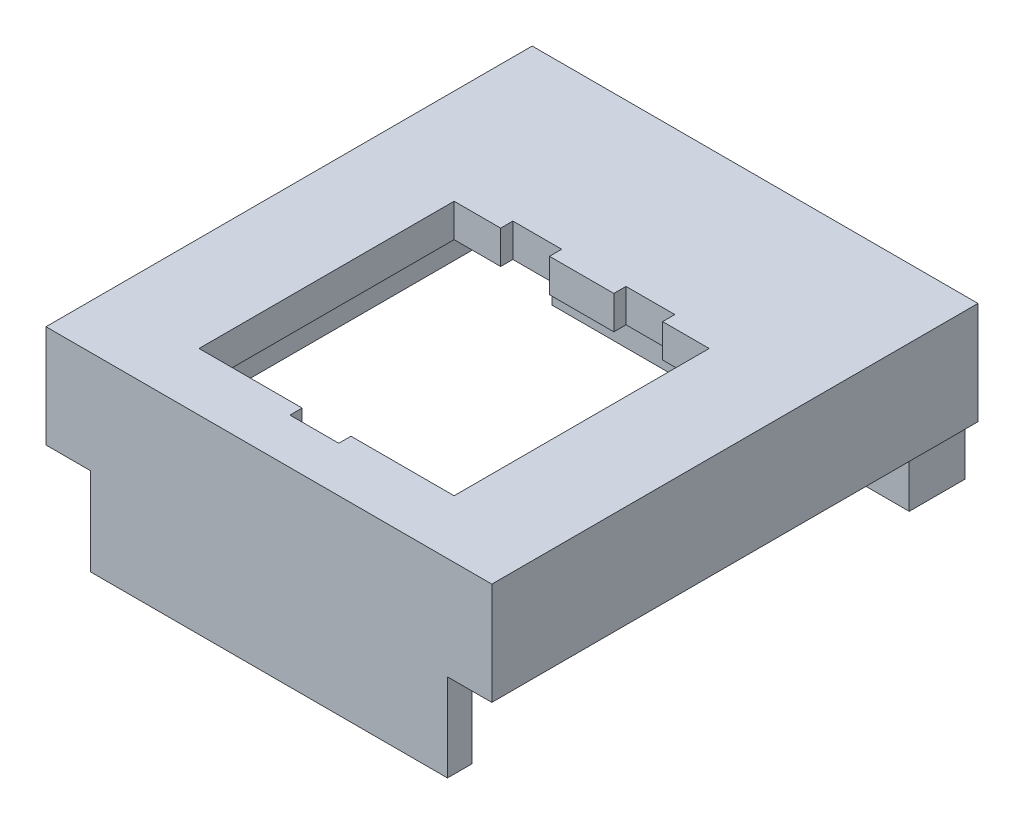
SolidWorks part; units mm, degrees
material "Custom Plastic"
ref_plane "Front Plane" through (0, 0, 0) normal (0, 0, 1) x (1, 0, 0)
ref_plane "Top Plane" through (0, 0, 0) normal (0, 1, 0) x (1, 0, 0)
ref_plane "Right Plane" through (0, 0, 0) normal (1, 0, 0) x (0, 0, -1)
sketch "Sketch1" plane through (0, 0, 0) normal (0, 1, 0) x (1, 0, 0)
  line L0 (-8.05, 10.21) -> (-8.05, -10.21)
  line L1 (8.05, -10.21) -> (8.05, 10.21)
  line L3 (10.05, -10.21) -> (10.05, 10.21)
  line L4 (-10.05, 10.21) -> (-10.05, -10.21)
  line L5 (-8.05, -10.21) -> (-10.05, -10.21)
  line L6 (8.05, -10.21) -> (10.05, -10.21)
  line L7 (-8.05, 10.21) -> (-10.05, 10.21)
  line L8 (8.05, 10.21) -> (10.05, 10.21)
  dimension "D1" = 8.05
  dimension "D2" = 10.05
  dimension "D3" = 8.05
  dimension "D4" = 10.21
  dimension "D5" = 10.21
extrude "Boss-Extrude1" add sketch "Sketch1" along normal blind 4.62
sketch "Sketch2" plane through (0, 4.62, 0) normal (0, 1, 0) x (1, 0, 0)
  line L0 (-8.05, -10.21) -> (8.05, -10.21)
  line L1 (-8.05, -9.11) -> (8.05, -9.11)
  line L2 (8.05, 10.21) -> (8.05, -10.21) construction
  line L3 (-8.05, -10.21) -> (-8.05, 10.21) construction
  line L4 (8.05, -9.11) -> (8.05, -10.21)
  line L5 (-8.05, -10.21) -> (-8.05, -9.11)
  dimension "D1" = 1.1
extrude "Boss-Extrude2" add sketch "Sketch2" against normal blind 8.57
sketch "Sketch3" plane through (0, 4.62, 0) normal (0, 1, 0) x (1, 0, 0)
  line L0 (-10.05, 10.21) -> (10.05, 10.21)
  line L2 (10.05, 11.71) -> (-10.05, 11.71)
  line L4 (-10.05, 10.21) -> (-10.05, 11.71)
  line L6 (10.05, 10.21) -> (10.05, 11.71)
  dimension "D1" = 1.5
extrude "Boss-Extrude3" add sketch "Sketch3" against normal blind 4.62
sketch "Sketch4" plane through (0, 0, 0) normal (0, -1, 0) x (1, 0, 0)
  line L0 (-8.05, -10.21) -> (8.05, -10.21) construction
  line L1 (-8.05, -10.21) -> (8.05, -10.21)
  line L2 (-8.05, -10.21) -> (-8.05, -11.71)
  line L3 (10.05, -11.71) -> (-10.05, -11.71) construction
  line L4 (-8.05, -11.71) -> (8.05, -11.71)
  line L5 (8.05, -11.71) -> (8.05, -10.21)
extrude "Boss-Extrude4" add sketch "Sketch4" along normal blind 3.95
sketch "Sketch5" plane through (-8.05, 0, 0) normal (1, 0, 0) x (0, 0, -1)
  line L0 (-9.11, 3.12) -> (10.21, 3.12)
  line L4 (-9.11, 4.62) -> (-9.11, 0)
  line L5 (-9.11, 0) -> (10.21, 0)
  line L6 (10.21, 0) -> (10.21, 4.62)
  line L7 (10.21, 4.62) -> (-9.11, 4.62)
  line L8 (-9.11, 4.62) -> (-9.11, 3.12)
  line L10 (10.21, 3.12) -> (10.21, 4.62)
  line L11 (10.21, 4.62) -> (-9.11, 4.62)
  dimension "D2" = 1.5
  dimension "D1" = 0
extrude "Boss-Extrude5" add sketch "Sketch5" along normal up to surface (16.1 mm away) up to face at (8.05, 2.31, -0.55)
sketch "Sketch6" plane through (0, 4.62, 0) normal (0, 1, 0) x (1, 0, 0)
  line L0 (5.75, -7.61) -> (-5.75, -7.61)
  line L1 (5.75, -7.61) -> (5.75, 3.89)
  line L2 (-5.75, 3.89) -> (5.75, 3.89)
  line L3 (-5.75, -7.61) -> (-5.75, 3.89)
  line L5 (-10.05, -10.21) -> (10.05, -10.21) construction
  line L6 (8.05, 10.21) -> (8.05, -9.11) construction
  dimension "D1" = 11.5
  dimension "D2" = 11.5
  dimension "D3" = 2.6
  dimension "D4" = 2.3
extrude "Cut-Extrude1" cut sketch "Sketch6" against normal through all
sketch "Sketch8" plane through (0, 4.62, 0) normal (0, 1, 0) x (1, 0, 0)
  line L0 (-5.75, -7.61) -> (5.75, -7.61) construction
  line L1 (-1.1, -7.61) -> (1.1, -7.61)
  line L2 (-1.1, -7.61) -> (-1.1, -8.16)
  line L3 (-1.1, -8.16) -> (1.1, -8.16)
  line L4 (1.1, -7.61) -> (1.1, -8.16)
  line L5 (-3.65, 4.44) -> (-1.45, 4.44)
  line L6 (-3.65, 4.44) -> (-3.65, 3.89)
  line L7 (-3.65, 3.89) -> (-1.45, 3.89)
  line L8 (-1.45, 4.44) -> (-1.45, 3.89)
  line L9 (1.45, 4.44) -> (3.65, 4.44)
  line L10 (1.45, 4.44) -> (1.45, 3.89)
  line L11 (1.45, 3.89) -> (3.65, 3.89)
  line L12 (3.65, 4.44) -> (3.65, 3.89)
  line L13 (5.75, 3.89) -> (-5.75, 3.89) construction
  point P6 (0, -7.61)
  point P20 (1.45, 4.165)
  dimension "D1" = 0.55
  dimension "D2" = 2.2
  dimension "D3" = 0.55
  dimension "D4" = 2.2
  dimension "D5" = 2.2
  dimension "D6" = 0.55
  dimension "D7" = 2.9
  dimension "D8" = 1.45
extrude "Cut-Extrude2" cut sketch "Sketch8" against normal blind 3.95
sketch "Sketch10" plane through (0, 0, -11.71) normal (0, 0, -1) x (-1, 0, 0)
  line L0 (4.4811, -0.9711) -> (4.4811, 2.1)
  line L1 (4.4811, -0.9711) -> (-3.64, -0.9711)
  line L2 (4.4811, 2.1) -> (-3.64, 2.1)
  line L3 (-3.64, 2.1) -> (-3.64, -0.9711)
  line L4 (-10.05, 4.62) -> (10.05, 4.62) construction
  line L5 (-10.05, 0) -> (-10.05, 4.62) construction
  dimension "D1" = 3.0711
  dimension "D2" = 8.1211
  dimension "D3" = 2.52
  dimension "D4" = 6.41
extrude "Cut-Extrude3" cut sketch "Sketch10" against normal blind 1.5
sketch "Sketch11" plane through (0, 0, -11.71) normal (0, 0, -1) x (-1, 0, 0)
  line L0 (-8.05, -3.95) -> (-8.05, 0) construction
  line L1 (-8.05, -3.95) -> (-8.05, -1.65)
  line L2 (8.05, -3.95) -> (8.05, 0) construction
  line L3 (8.05, -3.95) -> (8.05, -1.65)
  line L4 (8.05, -3.95) -> (-8.05, -3.95) construction
  line L5 (8.05, -3.95) -> (-8.05, -3.95)
  line L6 (-8.05, -1.65) -> (8.05, -1.65)
  dimension "D1" = 2.3
extrude "Boss-Extrude6" add sketch "Sketch11" along normal blind 2.08
sketch "Sketch12" plane through (0, -3.95, 0) normal (0, -1, 0) x (1, 0, 0)
  line L0 (8.05, -10.61) -> (-8.05, -10.61)
  line L4 (-8.05, -10.21) -> (-8.05, -13.79)
  line L5 (-8.05, -13.79) -> (8.05, -13.79)
  line L6 (8.05, -13.79) -> (8.05, -10.21)
  line L7 (8.05, -10.21) -> (-8.05, -10.21)
  line L8 (-8.05, -10.21) -> (-8.05, -10.61)
  line L10 (8.05, -10.61) -> (8.05, -10.21)
  line L11 (8.05, -10.21) -> (-8.05, -10.21)
  dimension "D1" = 0
  dimension "D2" = 0.4
extrude "Cut-Extrude5" cut sketch "Sketch12" against normal up to surface (7.07 mm away)
sketch "Sketch13" plane through (-8.05, 0, 0) normal (-1, 0, 0) x (0, 0, 1)
  line L0 (-10.61, -3.95) -> (-13.79, -3.95) construction
  line L1 (-13.79, -1.65) -> (-11.71, -1.65) construction
  line L2 (-13.79, -3.95) -> (-13.79, -1.65) construction
  line L3 (-13.59, -3.95) -> (-13.79, -3.95)
  line L4 (-13.79, -1.65) -> (-13.59, -1.65)
  line L5 (-13.79, -3.95) -> (-13.79, -1.65)
  line L6 (-13.59, -3.95) -> (-13.59, -1.65)
  dimension "D1" = 0.2
extrude "Cut-Extrude6" cut sketch "Sketch13" against normal through all both and the other way through all
sketch "Sketch14" plane through (-8.05, 0, 0) normal (-1, 0, 0) x (0, 0, 1)
  line L0 (-13.116, -3.95) -> (-13.116, -1.65)
  line L6 (-11.71, -1.65) -> (-13.59, -1.65)
  line L7 (-13.59, -1.65) -> (-13.59, -3.95)
  line L8 (-13.59, -3.95) -> (-10.61, -3.95)
  line L9 (-10.61, -3.95) -> (-10.61, 0)
  line L10 (-10.61, 0) -> (-11.71, 0)
  line L11 (-11.71, 0) -> (-11.71, -1.65)
  line L12 (-13.116, -1.65) -> (-13.59, -1.65)
  line L13 (-13.59, -1.65) -> (-13.59, -3.95)
  line L14 (-13.59, -3.95) -> (-13.116, -3.95)
  line L16 (-10.61, 0) -> (-11.71, 0)
  line M7 (-11.71, -1.65) -> (-13.59, -1.65)
  line M8 (-13.59, -1.65) -> (-13.59, -3.95)
  line M9 (-13.59, -3.95) -> (-10.61, -3.95)
  dimension "D1" = 0
extrude "Cut-Extrude8" cut sketch "Sketch14" against normal through all contours L0 M9 M7 M8
